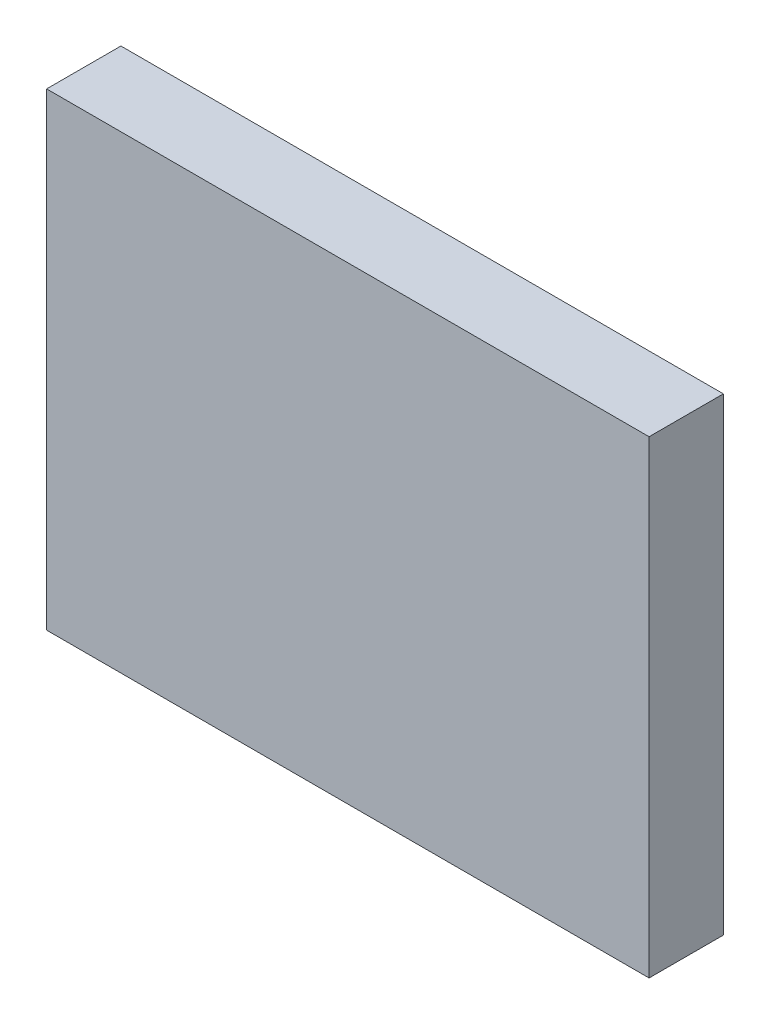
SolidWorks part; units mm, degrees
ref_plane "Front Plane" through (0, 0, 0) normal (0, 0, 1) x (1, 0, 0)
ref_plane "Top Plane" through (0, 0, 0) normal (0, 1, 0) x (1, 0, 0)
ref_plane "Right Plane" through (0, 0, 0) normal (1, 0, 0) x (0, 0, -1)
sketch "Sketch1" plane through (0, 0, 0) normal (0, 0, 1) x (1, 0, 0)
  line L0 (-3.65, 2.88) -> (3.65, 2.88)
  line L1 (3.65, 2.88) -> (3.65, -2.8)
  line L2 (3.65, -2.8) -> (-3.65, -2.8)
  line L3 (-3.65, -2.8) -> (-3.65, 2.88)
extrude "Component_Outline" add sketch "Sketch1" along normal blind 0.9 separate body
sketch3d "3DSketch1"
  line L0 (0, 0, 0) -> (1, 0, 0)
  line L1 (0, 0, 0) -> (0, 1, 0)
  line L2 (0, 0, 0) -> (0, 0, 1)
  point P0 (0, 0, 0)
